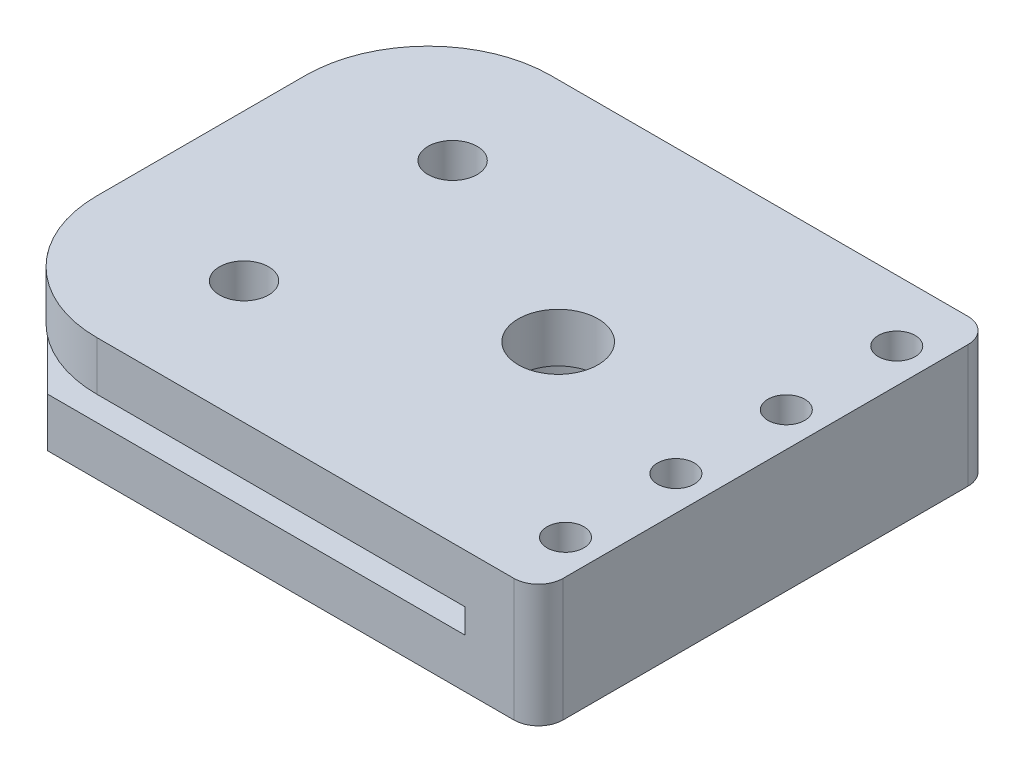
SolidWorks part; units mm, degrees
ref_plane "Front Plane" through (0, 0, 0) normal (0, 0, 1) x (1, 0, 0)
ref_plane "Top Plane" through (0, 0, 0) normal (0, 1, 0) x (1, 0, 0)
ref_plane "Right Plane" through (0, 0, 0) normal (1, 0, 0) x (0, 0, -1)
sketch "Sketch1" plane through (0, 0, 0) normal (0, 1, 0) x (1, 0, 0)
  line L1 (-25, -18.5) -> (25, -18.5)
  line L2 (-25, -18.5) -> (-25, 18.5)
  line L3 (-25, 18.5) -> (25, 18.5)
  line L4 (25, -18.5) -> (25, 18.5)
  line L5 (-25, -18.5) -> (25, 18.5) construction
  line L6 (-25, 18.5) -> (25, -18.5) construction
  point P0 (0, 0)
  dimension "D1" = 37
  dimension "D2" = 50
extrude "Boss-Extrude1" add sketch "Sketch1" along normal blind 4
chamfer "Chamfer1" distance 10 angle 45 2 edges at (-25, 2, 18.5) (-25, 2, -18.5)
sketch "Sketch2" plane through (0, 4, 0) normal (0, 1, 0) x (1, 0, 0)
  line L0 (-15, -18.5) -> (25, -18.5) construction
  line L1 (25, 18.5) -> (19, 18.5)
  line L2 (25, 18.5) -> (25, -18.5)
  line L3 (25, -18.5) -> (19, -18.5)
  line L4 (19, 18.5) -> (19, -18.5)
  dimension "D1" = 6
extrude "Boss-Extrude2" add sketch "Sketch2" along normal blind 6
sketch "Sketch3" plane through (19, 0, 0) normal (-1, 0, 0) x (0, 0, 1)
  line L0 (18.5, 10) -> (18.5, 4) construction
  line L1 (-18.5, 10) -> (18.5, 10)
  line L2 (-18.5, 10) -> (-18.5, 6)
  line L3 (-18.5, 6) -> (18.5, 6)
  line L4 (18.5, 10) -> (18.5, 6)
  dimension "D1" = 4
extrude "Boss-Extrude3" add sketch "Sketch3" along normal blind 40
fillet "Fillet1" radius 10 2 edges at (-21, 8, 18.5) (-21, 8, -18.5)
sketch "Sketch4" plane through (0, 10, 0) normal (0, 1, 0) x (1, 0, 0)
  line L0 (19, 18.5) -> (19, -18.5) construction
  line L1 (25, 18.5) -> (-11, 18.5) construction
  line L2 (-11, -18.5) -> (25, -18.5) construction
  circle A0 centre (-9, -8.5) radius 2
  circle A1 centre (-9, 8.5) radius 2
  dimension "D1" = 4
  dimension "D2" = 4
  dimension "D3" = 28
  dimension "D4" = 28
  dimension "D5" = 10
  dimension "D6" = 10
extrude "Cut-Extrude1" cut sketch "Sketch4" against normal blind 40
sketch "Sketch5" plane through (0, 10, 0) normal (0, 1, 0) x (1, 0, 0)
  circle A0 centre (8.1026, 0) radius 3.25
  dimension "D1" = 6.5
extrude "Cut-Extrude2" cut sketch "Sketch5" against normal blind 40
sketch "Sketch6" plane through (0, 0, 0) normal (0, -1, 0) x (1, 0, 0)
  circle A0 centre (8.1026, 0) radius 7.5
  dimension "D1" = 15
extrude "Cut-Extrude3" cut sketch "Sketch6" against normal blind 5
sketch "Sketch7" plane through (0, 10, 0) normal (0, 1, 0) x (1, 0, 0)
  line L0 (-11, -18.5) -> (25, -18.5) construction
  line L1 (25, 18.5) -> (-11, 18.5) construction
  line L2 (25, -18.5) -> (25, 18.5) construction
  circle A0 centre (22.2, 13.5) radius 1.5
  circle A1 centre (22.2, 4.5) radius 1.5
  circle A2 centre (22.2, -4.5) radius 1.5
  circle A3 centre (22.2, -13.5) radius 1.5
  dimension "D1" = 3
  dimension "D2" = 3
  dimension "D3" = 3
  dimension "D4" = 3
  dimension "D5" = 5
  dimension "D6" = 5
  dimension "D7" = 9
  dimension "D8" = 9
  dimension "D9" = 2.8
  dimension "D10" = 2.8
  dimension "D11" = 2.8
extrude "Cut-Extrude4" cut sketch "Sketch7" against normal blind 9
fillet "Fillet2" radius 2 2 edges at (25, 5, 18.5) (25, 5, -18.5)
